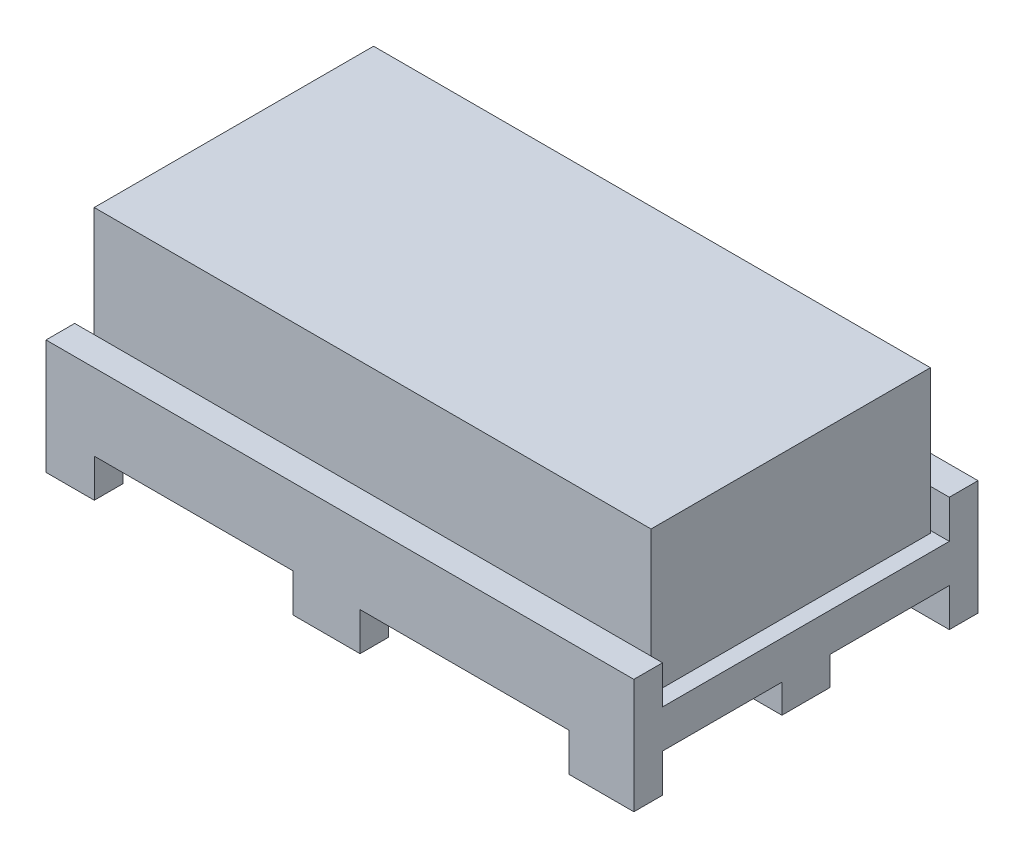
SolidWorks part; units mm, degrees
ref_plane "Front Plane" through (0, 0, 0) normal (0, 0, 1) x (1, 0, 0)
ref_plane "Top Plane" through (0, 0, 0) normal (0, 1, 0) x (1, 0, 0)
ref_plane "Right Plane" through (0, 0, 0) normal (1, 0, 0) x (0, 0, -1)
sketch "Sketch1" plane through (0, 0, 0) normal (0, 1, 0) x (1, 0, 0)
  line L0 (52.07, 0) -> (-52.07, 0) construction
  line L1 (-52.07, -19.05) -> (52.07, -19.05)
  line L2 (-52.07, -19.05) -> (-52.07, 19.05)
  line L3 (-52.07, 19.05) -> (52.07, 19.05)
  line L4 (52.07, -19.05) -> (52.07, 19.05)
  line L5 (-52.07, -19.05) -> (52.07, 19.05) construction
  line L6 (-52.07, 19.05) -> (52.07, -19.05) construction
  line L7 (-52.07, 22.86) -> (52.07, 22.86)
  line L8 (-52.07, 22.86) -> (-52.07, -22.86)
  line L9 (-52.07, -22.86) -> (52.07, -22.86)
  line L10 (52.07, 22.86) -> (52.07, -22.86)
  point P0 (0, 0)
  dimension "D1" = 38.1
  dimension "D2" = 104.14
  dimension "D3" = 3.81
extrude "Boss-Extrude1" add sketch "Sketch1" along normal blind 5.08 contours L10 L1 L8 L9 | L10 L7 L8 L3
sketch "Sketch2" plane through (0, 5.08, 0) normal (0, 1, 0) x (1, 0, 0)
  line L1 (-52.07, 22.86) -> (52.07, 22.86)
  line L2 (-52.07, 22.86) -> (-52.07, -22.86)
  line L3 (-52.07, -22.86) -> (52.07, -22.86)
  line L4 (52.07, 22.86) -> (52.07, -22.86)
extrude "Boss-Extrude2" add sketch "Sketch2" along normal blind 5.08
sketch "Sketch3" plane through (0, 10.16, 0) normal (0, 1, 0) x (1, 0, 0)
  line L0 (52.07, 0) -> (-52.07, 0) construction
  line L1 (-52.07, -19.05) -> (52.07, -19.05)
  line L2 (-52.07, -19.05) -> (-52.07, 19.05)
  line L3 (-52.07, 19.05) -> (52.07, 19.05)
  line L4 (52.07, -19.05) -> (52.07, 19.05)
  line L5 (-52.07, -19.05) -> (52.07, 19.05) construction
  line L6 (-52.07, 19.05) -> (52.07, -19.05) construction
  line L7 (-52.07, 22.86) -> (52.07, 22.86)
  line L8 (-52.07, 22.86) -> (-52.07, -22.86)
  line L9 (-52.07, -22.86) -> (52.07, -22.86)
  line L10 (52.07, 22.86) -> (52.07, -22.86)
  point P0 (0, 0)
  line M9 (-52.07, 22.86) -> (-52.07, -22.86)
  line M10 (-52.07, -22.86) -> (52.07, -22.86)
  line M11 (52.07, -22.86) -> (52.07, 22.86)
  line M12 (52.07, 22.86) -> (-52.07, 22.86)
  dimension "D1" = 38.1
  dimension "D2" = 104.14
  dimension "D3" = 3.81
extrude "Boss-Extrude3" add sketch "Sketch3" along normal blind 5.08 contours L3 M9 M11 M12 | L1 M9 M10 M11
sketch "Sketch4" plane through (0, 5.08, 0) normal (0, -1, 0) x (1, 0, 0)
  line L0 (52.07, 19.05) -> (52.07, -19.05) construction
  line L1 (-52.07, -3.1877) -> (52.07, -3.1877)
  line L2 (-52.07, -3.1877) -> (-52.07, 3.1877)
  line L3 (-52.07, 3.1877) -> (52.07, 3.1877)
  line L4 (52.07, -3.1877) -> (52.07, 3.1877)
  line L5 (-52.07, -3.1877) -> (52.07, 3.1877) construction
  line L6 (-52.07, 3.1877) -> (52.07, -3.1877) construction
  point P0 (0, 0)
  dimension "D1" = 6.3754
extrude "Boss-Extrude4" add sketch "Sketch4" along normal blind 3.81
sketch "Sketch5" plane through (0, 0, 22.86) normal (0, 0, 1) x (1, 0, 0)
  line L0 (-52.07, 0) -> (52.07, 0) construction
  line L1 (-45.6558, 0) -> (-19.2872, 0)
  line L2 (-45.6558, 0) -> (-45.6558, 5.08)
  line L3 (-45.6558, 5.08) -> (-19.2872, 5.08)
  line L4 (-19.2872, 0) -> (-19.2872, 5.08)
  line L6 (-10.348, 0) -> (17.4085, 0)
  line L7 (-10.348, 0) -> (-10.348, 5.08)
  line L8 (-10.348, 5.08) -> (17.4085, 5.08)
  line L9 (17.4085, 0) -> (17.4085, 5.08)
  line L10 (26.0257, 20.6101) -> (56.3311, 20.6101)
  line L11 (26.0257, 20.6101) -> (26.0257, -5.4351)
  line L12 (26.0257, -5.4351) -> (56.3311, -5.4351)
  line L13 (56.3311, 20.6101) -> (56.3311, -5.4351)
  dimension "D1" = 5.08
  dimension "D2" = 5.08
extrude "Cut-Extrude1" cut sketch "Sketch5" against normal through all both and the other way through all
sketch "Sketch6" plane through (0, 10.16, 0) normal (0, 1, 0) x (1, 0, 0)
  line L1 (-50.1356, 18.7251) -> (23.8388, 18.7251)
  line L2 (-50.1356, 18.7251) -> (-50.1356, -18.3884)
  line L3 (-50.1356, -18.3884) -> (23.8388, -18.3884)
  line L4 (23.8388, 18.7251) -> (23.8388, -18.3884)
extrude "Boss-Extrude5" add sketch "Sketch6" along normal blind 19.05
